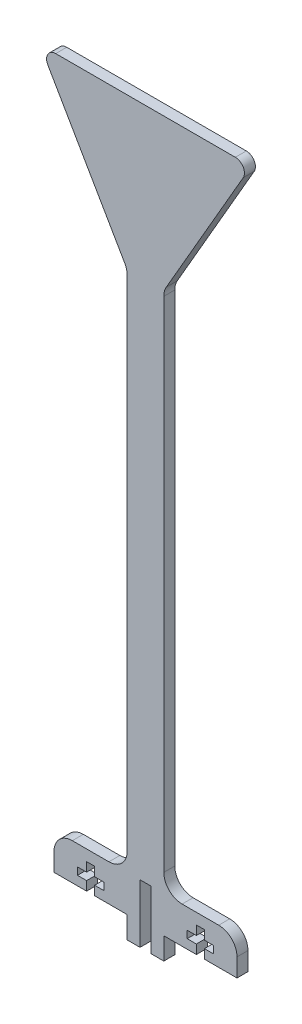
SolidWorks part; units mm, degrees
ref_plane "Front Plane" through (0, 0, 0) normal (0, 0, 1) x (1, 0, 0)
ref_plane "Top Plane" through (0, 0, 0) normal (0, 1, 0) x (1, 0, 0)
ref_plane "Right Plane" through (0, 0, 0) normal (1, 0, 0) x (0, 0, -1)
sketch "Sketch1" plane through (0, 0, 0) normal (0, 0, 1) x (1, 0, 0)
  line L0 (-5, -25) -> (-5, -159)
  line L7 (-5, -175) -> (-1.5, -175)
  line L8 (5, -175) -> (5, -169)
  line L10 (-5, -169) -> (-13.9, -169)
  line L11 (-25, -169) -> (-25, -159)
  line L12 (-25, -159) -> (-5, -159)
  line L13 (-16.1, -169) -> (-16.1, -166.5)
  line L14 (0, 25) -> (0, -175) construction
  line L15 (-16.1, -166.5) -> (-18.6, -166.5)
  line L16 (-18.6, -166.5) -> (-18.6, -164.5)
  line L17 (-18.6, -164.5) -> (-16.1, -164.5)
  line L18 (-16.1, -164.5) -> (-16.1, -162)
  line L19 (-16.1, -162) -> (-13.9, -162)
  line L20 (-13.9, -162) -> (-13.9, -164.5)
  line L21 (-13.9, -164.5) -> (-11.4, -164.5)
  line L22 (-11.4, -164.5) -> (-11.4, -166.5)
  line L23 (-11.4, -166.5) -> (-13.9, -166.5)
  line L24 (-13.9, -166.5) -> (-13.9, -169)
  line L25 (-15, -159) -> (-15, -169) construction
  line L26 (15, -159) -> (15, -169) construction
  line L27 (13.9, -166.5) -> (13.9, -169)
  line L28 (11.4, -166.5) -> (13.9, -166.5)
  line L29 (11.4, -164.5) -> (11.4, -166.5)
  line L30 (13.9, -164.5) -> (11.4, -164.5)
  line L31 (13.9, -162) -> (13.9, -164.5)
  line L32 (16.1, -162) -> (13.9, -162)
  line L33 (16.1, -164.5) -> (16.1, -162)
  line L34 (18.6, -164.5) -> (16.1, -164.5)
  line L35 (18.6, -166.5) -> (18.6, -164.5)
  line L36 (16.1, -166.5) -> (18.6, -166.5)
  line L37 (16.1, -169) -> (16.1, -166.5)
  line L38 (25, -159) -> (5, -159)
  line L39 (25, -169) -> (25, -159)
  line L40 (5, -169) -> (13.9, -169)
  line L41 (-16.1, -169) -> (-25, -169)
  line L42 (16.1, -169) -> (25, -169)
  line L43 (5, -159) -> (5, -25)
  line L44 (-5, -169) -> (-5, -175)
  line L45 (-1.5, -175) -> (-1.5, -159)
  line L46 (-1.5, -159) -> (1.5, -159)
  line L47 (1.5, -159) -> (1.5, -175)
  line L48 (1.5, -175) -> (5, -175)
  line L49 (0, 25) -> (-28.8675, 25)
  line L50 (0, 25) -> (28.8675, 25)
  line L51 (-5, -25) -> (5, -25) construction
  line L52 (-28.8675, 25) -> (-5, -16.3397)
  line L53 (5, -16.3397) -> (28.8675, 25)
  line L54 (-5, -25) -> (-5, -16.3397)
  line L55 (5, -25) -> (5, -16.3397)
  point P0 (0, 0)
  point P36 (-15, -162)
  point P57 (0, -159)
  dimension "D3" = 200
  dimension "D2" = 25
  dimension "D4" = 25
  dimension "D5" = 5
  dimension "D8" = 150
  dimension "D9" = 10
  dimension "D10" = 20
  dimension "D11" = 6
  dimension "D12" = 2.5
  dimension "D13" = 2
  dimension "D14" = 2.5
  dimension "D15" = 2.5
  dimension "D16" = 2.2
  dimension "D17" = 2.5
  dimension "D18" = 16
  dimension "D19" = 1.5
  dimension "D20" = 28.8675
  dimension "D21" = 28.8675
  dimension "D22" = 25
extrude "Boss-Extrude1" add sketch "Sketch1" along normal blind 3
fillet "Fillet1" radius 5 6 edges at (-5, -159, 1.5) (5, -159, 1.5) (25, -159, 1.5) (-25, -159, 1.5) (-5, -16.3397, 1.5) (5, -16.3397, 1.5)
fillet "Fillet2" radius 2.5 2 edges at (-28.8675, 25, 1.5) (28.8675, 25, 1.5)
